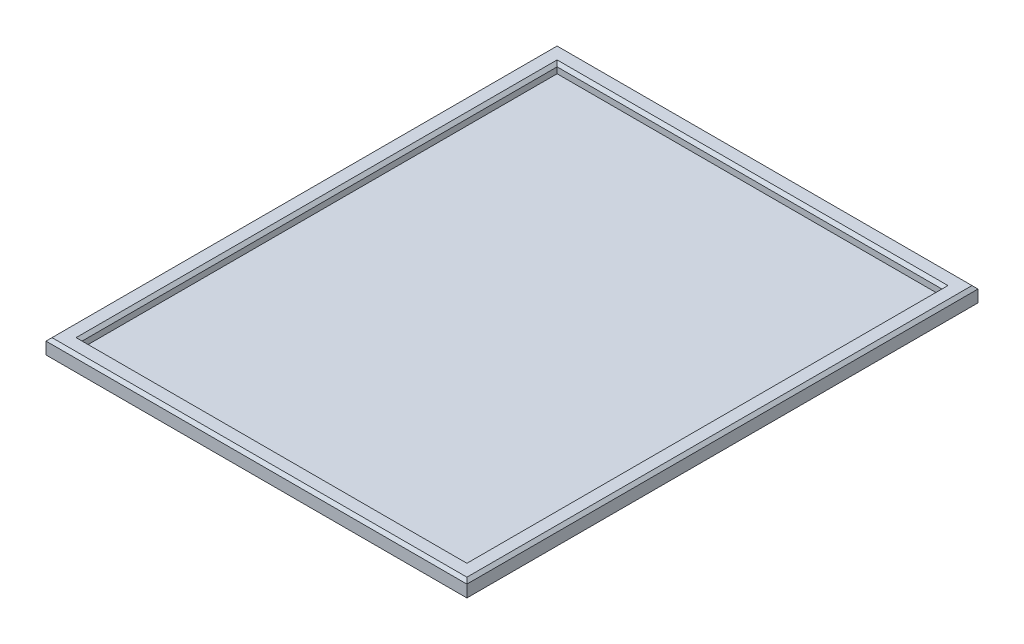
SolidWorks part; units mm, degrees
material "MDF wood"
ref_plane "Front Plane" through (0, 0, 0) normal (0, 0, 1) x (1, 0, 0)
ref_plane "Top Plane" through (0, 0, 0) normal (0, 1, 0) x (1, 0, 0)
ref_plane "Right Plane" through (0, 0, 0) normal (1, 0, 0) x (0, 0, -1)
sketch "Sketch3" plane through (0, 0, 0) normal (0, 1, 0) x (1, 0, 0)
  line L0 (-320, 395) -> (320, 395)
  line L1 (-350, -425) -> (350, -425)
  line L2 (-350, -425) -> (-350, 425)
  line L3 (-350, 425) -> (350, 425)
  line L4 (350, -425) -> (350, 425)
  line L5 (-350, -425) -> (350, 425) construction
  line L6 (-350, 425) -> (350, -425) construction
  line L7 (320, -395) -> (320, 395)
  line L8 (-320, -395) -> (320, -395)
  line L9 (-320, -395) -> (-320, 395)
  point P0 (0, 0)
  dimension "D1" = 700
  dimension "D2" = 850
  dimension "D3" = 30
extrude "Boss-Extrude1" add sketch "Sketch3" along normal blind 30
chamfer "Chamfer2" distance 5 angle 45 12 edges at (0, 0, -425) (-350, 0, 0) (0, 0, 425) (350, 0, 0) (0, 30, 395) (320, 30, 0) (0, 30, -395) (-320, 30, 0) (0, 30, 425) (-350, 30, 0) (0, 30, -425) (350, 30, 0)
sketch "Sketch4" plane through (0, 0, 0) normal (0, -1, 0) x (1, 0, 0)
  line L0 (320, 395) -> (320, -395) construction
  line L1 (320, -395) -> (-320, -395) construction
  line L2 (-320, -395) -> (-320, 395) construction
  line L3 (-320, 395) -> (320, 395) construction
  line L12 (320, 395) -> (320, -395)
  line L13 (320, -395) -> (-320, -395)
  line L14 (-320, -395) -> (-320, 395)
  line L15 (-320, 395) -> (320, 395)
extrude "Boss-Extrude2" add sketch "Sketch4" against normal blind 15 separate body
